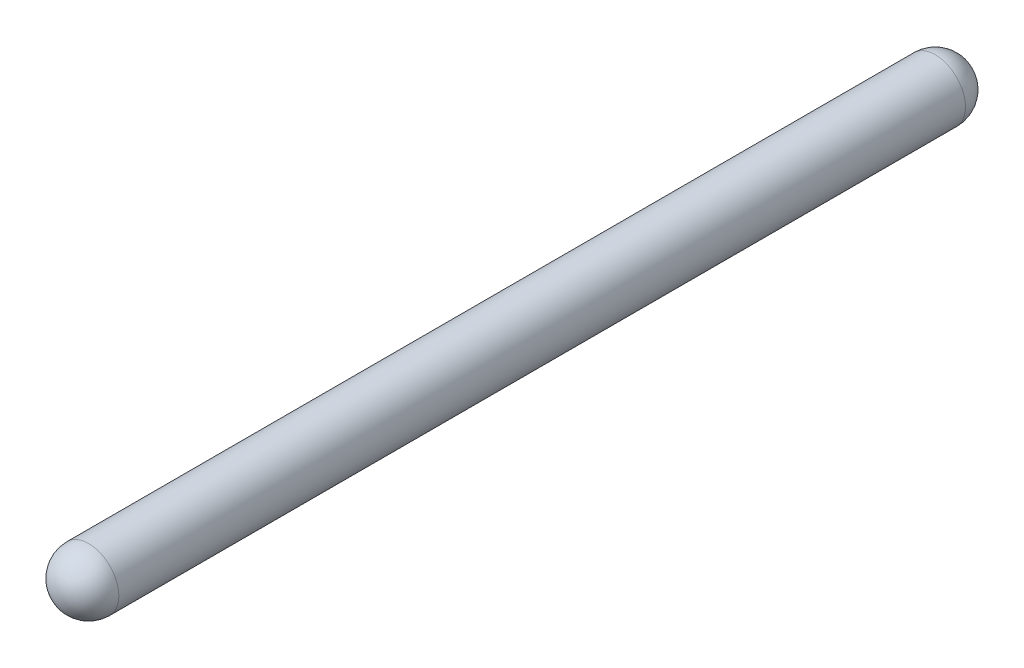
SolidWorks part; units mm, degrees
material "AISI 4130 Steel, normalized at 870C"
ref_plane "Front Plane" through (0, 0, 0) normal (0, 0, 1) x (1, 0, 0)
ref_plane "Top Plane" through (0, 0, 0) normal (0, 1, 0) x (1, 0, 0)
ref_plane "Right Plane" through (0, 0, 0) normal (1, 0, 0) x (0, 0, -1)
sketch "Sketch2" plane through (0, 0, 0) normal (0, 0, 1) x (1, 0, 0)
  circle A0 centre (0, 0) radius 1
extrude "Boss-Extrude4" add sketch "Sketch2" along normal blind 30
fillet "Fillet2" radius 1 2 edges at (1, 0, 0) (1, 0, 30)
scale "Escala1" scale about centroid uniform scaling yes scale factor 0.5
